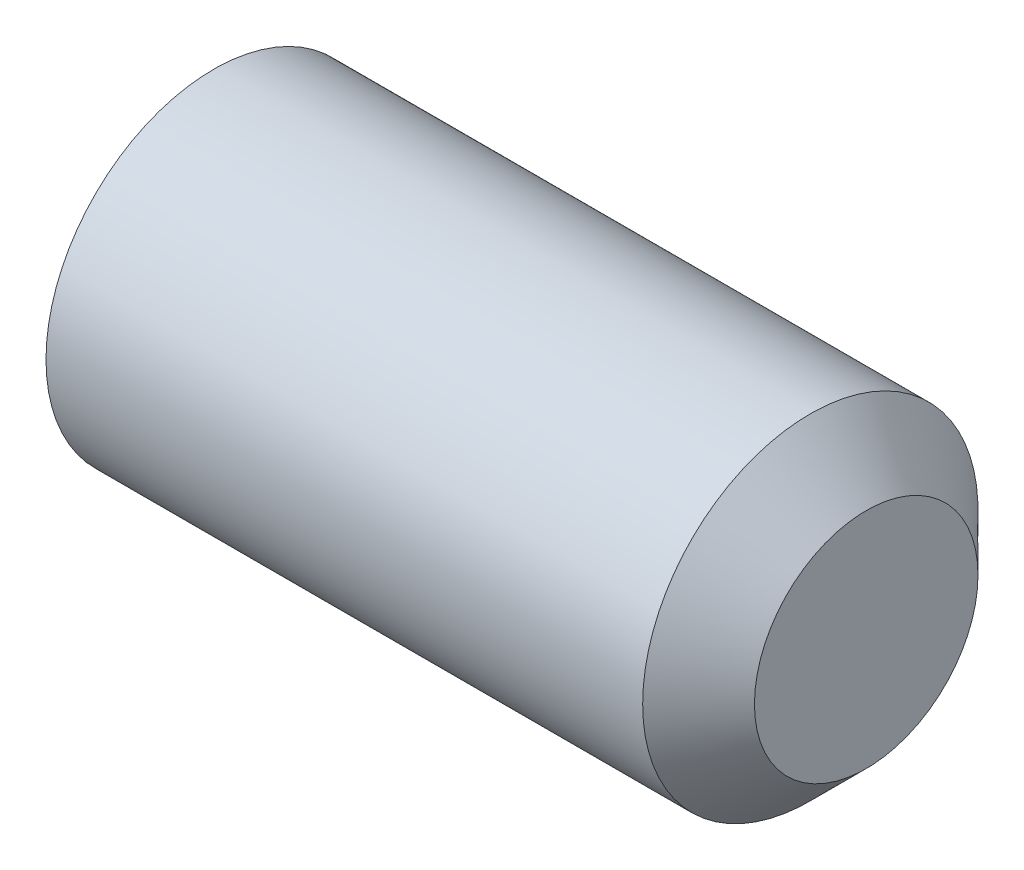
SolidWorks part; units mm, degrees
revolve "BaseBody" add sketch "BodySke" angle 360 about L5
sketch "BodySke" plane through (0, 0, 0) normal (0, 0, 1) x (1, 0, 0)
  line L0 (0, 0) -> (0, 1.2195)
  line L1 (0, 1.2195) -> (0.1619, 1.5)
  line L2 (0.1619, 1.5) -> (5.5, 1.5)
  line L3 (5.5, 1.5) -> (6, 1)
  line L4 (6, 0) -> (0, 0)
  line L5 (-12.7, 0) -> (88.9, 0) construction
  line L6 (6, 1) -> (6, 0)
  line L7 (6, 1) -> (6, 10.525) construction
  line L8 (0, -1.2195) -> (0.1619, -1.5) construction
  line L9 (0.5, 15.875) -> (0.5, -3.175) construction
  line L10 (5.5, -1.5) -> (6, -1) construction
  dimension "Diameter" = 3
  dimension "Drive_ch_ang" = 60
  dimension "Minor_dia" = 2.439
  dimension "Cup_nose_ang" = 45
  dimension "Cup_dia" = 2
  dimension "Length" = 6
  dimension "Advance" = 0.5
cosmetic thread "ThreadCosmetic" [suppressed] parameters "Thread_minor"=2.439
ref_plane "Plane1" through (0, 0, 0) normal (0, 0, 1) x (1, 0, 0)
ref_plane "Plane2" through (0, 0, 0) normal (0, 1, 0) x (1, 0, 0)
ref_plane "Plane3" through (0, 0, 0) normal (1, 0, 0) x (0, 0, -1)
other "Configuration Table"
sketch "Sketch2" plane through (0, 0, 0) normal (-1, 0, 0) x (0, 0, 1)
  line L0 (0.433, 0.75) -> (-0.433, 0.75)
  line L1 (-0.433, 0.75) -> (-0.866, 0)
  line L2 (0.433, 0.75) -> (0.866, 0)
  line L3 (0.433, -0.75) -> (0.866, 0)
  line L4 (0.433, -0.75) -> (-0.433, -0.75)
  line L5 (-0.433, -0.75) -> (-0.866, 0)
  dimension "Hex_size" = 1.5
  dimension "D2" = 0.75
  dimension "D3" = 0.75
extrude "Hex" cut sketch "Sketch2" against normal blind 2
sketch "ThdSchSke" plane through (0, 0, 0) normal (0, 0, 1) x (1, 0, 0)
  line L0 (0.1619, -1.2195) -> (-0.0345, -1.5)
  line L1 (0.1619, -1.2195) -> (0.3584, -1.5)
  line L2 (0.3584, -1.5) -> (0.3584, -1.875)
  line L3 (-3.175, 0) -> (5.1513, 0) construction
  line L5 (0.3584, -1.875) -> (-0.0345, -1.875)
  line L6 (-0.0345, -1.875) -> (-0.0345, -1.5)
  line L8 (0.1619, 1.5) -> (0.1619, -1.5) construction
  dimension "Thread_minor" = 2.439
  dimension "Diameter" = 3
revolve "ThreadSchematic" [suppressed] cut sketch "ThdSchSke" angle 360 about L3
pattern_linear "ThdSchPat" [suppressed]
equation "\"D2@Sketch2\" = \"Hex_size@Sketch2\" / 2"
equation "\"D3@Sketch2\" = \"Hex_size@Sketch2\" / 2"
equation "\"Thread_minor@ThreadCosmetic\" = \"Minor_dia@BodySke\""
equation "\"Thread_minor@ThdSchSke\" = \"Thread_minor@ThreadCosmetic\""
equation "\"Diameter@ThdSchSke\" = \"Diameter@BodySke\""
equation "\"Overcut@ThdSchSke\" = \"Diameter@BodySke\" * 1.25"
equation "\"Num_threads@ThdSchPat\" = int( (\"Length@BodySke\" - ( ( ( \"Diameter@BodySke\" - \"Minor_dia@BodySke\" ) * 0.5 ) / tan( \"Drive_ch_ang@BodySke\" * 0.017453292 ) ) - ( ( ( \"Diameter@BodySke\" - \"Cup_dia@BodySke\" ) * 0.5 ) * tan( \"Cup_nose_ang@BodySke\" * 0.017453292 ) ) ) / \"Advance@BodySke\" + 0.999 )  + 1"
equation "\"Advance@ThdSchPat\" = (\"Length@BodySke\" - ( ( ( \"Diameter@BodySke\" - \"Minor_dia@BodySke\" ) * 0.5 ) / tan( \"Drive_ch_ang@BodySke\" * 0.017453292 ) ) - ( ( ( \"Diameter@BodySke\" - \"Cup_dia@BodySke\" ) * 0.5 ) * tan( \"Cup_nose_ang@BodySke\" * 0.017453292 ) ) ) /  (\"Num_threads@ThdSchPat\" - 1) 'relax it"
equation "' \"Num_threads@ThdSchPat\" = \"Num_threads@ThdSchPat\" - sgn( \"Num_threads@ThdSchPat\" - 1) '---chamfered tips only---"
